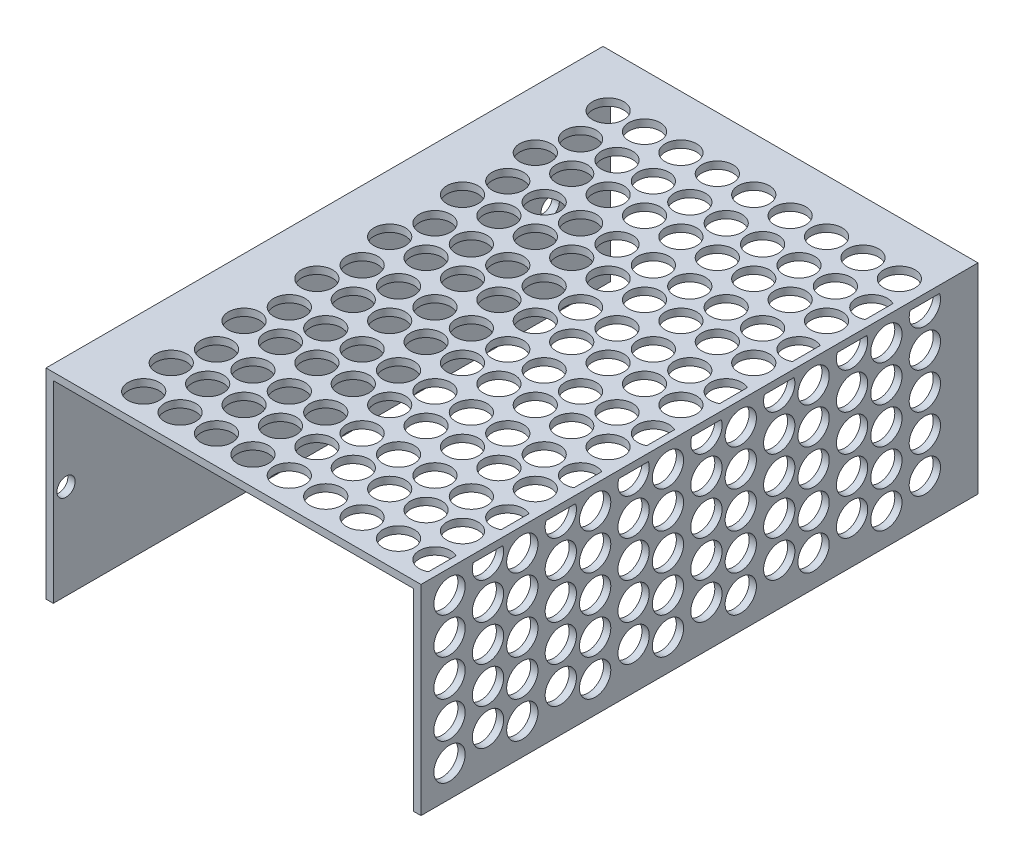
SolidWorks part; units mm, degrees
ref_plane "Спереди" through (0, 0, 0) normal (0, 0, 1) x (1, 0, 0)
ref_plane "Сверху" through (0, 0, 0) normal (0, 1, 0) x (1, 0, 0)
ref_plane "Справа" through (0, 0, 0) normal (1, 0, 0) x (0, 0, -1)
sketch "Эскиз1" plane through (0, 0, 0) normal (0, 0, 1) x (1, 0, 0)
  line L0 (50.5, 0) -> (50.5, 27.5)
  line L1 (50.5, 27.5) -> (1, 27.5)
  line L2 (1, 27.5) -> (1, 0)
  line L3 (0, 0) -> (1, 0)
  line L4 (51.5, 0) -> (51.5, 28.5)
  line L5 (51.5, 28.5) -> (0, 28.5)
  line L6 (0, 28.5) -> (0, 0)
  line L7 (50.5, 0) -> (51.5, 0)
extrude "Бобышка-Вытянуть1" add sketch "Эскиз1" along normal blind 78.5
sketch "Эскиз2" plane through (51.5, 0, 0) normal (1, 0, 0) x (0, 0, -1)
  line L0 (-77.5, 28.5) -> (-77.5, 1)
  line L1 (-78.5, 28.5) -> (0, 28.5) construction
  line L5 (-77.5, 1) -> (-1, 1)
  line L6 (0, 28.5) -> (-1, 28.5)
  line L7 (-1, 28.5) -> (-1, 1)
  line L9 (-77.5, 28.5) -> (-78.5, 28.5)
  line L10 (-78.5, 28.5) -> (-78.5, 0)
  line L12 (-78.5, 0) -> (0, 0)
  line L13 (0, 28.5) -> (0, 0)
extrude "Вырез-Вытянуть1" cut sketch "Эскиз2" against normal through all
sketch "Эскиз3" plane through (0, 28.5, 0) normal (0, 1, 0) x (1, 0, 0)
  line L0 (0, -77.5) -> (0, -1) construction
  line L1 (0, 0) -> (51.5, 0) construction
  line L2 (50.5, -21.6788) -> (50.5, -25.4853)
  line L4 (50.5, -31.6788) -> (50.5, -35.4853)
  line L5 (50.5, -11.6788) -> (50.5, -15.4853)
  line L6 (50.5, -41.6788) -> (50.5, -45.4853)
  line L7 (50.5, -51.6788) -> (50.5, -55.4853)
  line L8 (50.5, -61.6788) -> (50.5, -65.4853)
  line L9 (50.5, -71.6788) -> (50.5, -75.4853)
  circle A0 centre (8, -8.3) radius 2.15
  circle A1 centre (9.5, -13.582) radius 2.15
  circle A2 centre (13, -8.3) radius 2.15
  circle A3 centre (14.5, -13.582) radius 2.15
  circle A4 centre (18, -8.3) radius 2.15
  circle A5 centre (19.5, -13.582) radius 2.15
  circle A6 centre (23, -8.3) radius 2.15
  circle A7 centre (24.5, -13.582) radius 2.15
  circle A8 centre (28, -8.3) radius 2.15
  circle A9 centre (29.5, -13.582) radius 2.15
  circle A10 centre (33, -8.3) radius 2.15
  circle A11 centre (34.5, -13.582) radius 2.15
  circle A12 centre (38, -8.3) radius 2.15
  circle A13 centre (39.5, -13.582) radius 2.15
  circle A14 centre (43, -8.3) radius 2.15
  circle A15 centre (44.5, -13.582) radius 2.15
  circle A16 centre (48, -8.3) radius 2.15
  arc A17 (50.5, -11.6788) -> (50.5, -15.4853) centre (49.5, -13.582) ccw
  circle A18 centre (8, -18.3) radius 2.15
  circle A19 centre (9.5, -23.582) radius 2.15
  circle A20 centre (13, -18.3) radius 2.15
  circle A21 centre (14.5, -23.582) radius 2.15
  circle A22 centre (18, -18.3) radius 2.15
  circle A23 centre (19.5, -23.582) radius 2.15
  circle A24 centre (23, -18.3) radius 2.15
  circle A25 centre (24.5, -23.582) radius 2.15
  circle A26 centre (28, -18.3) radius 2.15
  circle A27 centre (29.5, -23.582) radius 2.15
  circle A28 centre (33, -18.3) radius 2.15
  circle A29 centre (34.5, -23.582) radius 2.15
  circle A30 centre (38, -18.3) radius 2.15
  circle A31 centre (39.5, -23.582) radius 2.15
  circle A32 centre (43, -18.3) radius 2.15
  circle A33 centre (44.5, -23.582) radius 2.15
  circle A34 centre (48, -18.3) radius 2.15
  arc A35 (50.5, -21.6788) -> (50.5, -25.4853) centre (49.5, -23.582) ccw
  circle A36 centre (8, -28.3) radius 2.15
  circle A37 centre (9.5, -33.582) radius 2.15
  circle A38 centre (13, -28.3) radius 2.15
  circle A39 centre (14.5, -33.582) radius 2.15
  circle A40 centre (18, -28.3) radius 2.15
  circle A41 centre (19.5, -33.582) radius 2.15
  circle A42 centre (23, -28.3) radius 2.15
  circle A43 centre (24.5, -33.582) radius 2.15
  circle A44 centre (28, -28.3) radius 2.15
  circle A45 centre (29.5, -33.582) radius 2.15
  circle A46 centre (33, -28.3) radius 2.15
  circle A47 centre (34.5, -33.582) radius 2.15
  circle A48 centre (38, -28.3) radius 2.15
  circle A49 centre (39.5, -33.582) radius 2.15
  circle A50 centre (43, -28.3) radius 2.15
  circle A51 centre (44.5, -33.582) radius 2.15
  circle A52 centre (48, -28.3) radius 2.15
  arc A53 (50.5, -31.6788) -> (50.5, -35.4853) centre (49.5, -33.582) ccw
  circle A54 centre (8, -38.3) radius 2.15
  circle A55 centre (9.5, -43.582) radius 2.15
  circle A56 centre (13, -38.3) radius 2.15
  circle A57 centre (14.5, -43.582) radius 2.15
  circle A58 centre (18, -38.3) radius 2.15
  circle A59 centre (19.5, -43.582) radius 2.15
  circle A60 centre (23, -38.3) radius 2.15
  circle A61 centre (24.5, -43.582) radius 2.15
  circle A62 centre (28, -38.3) radius 2.15
  circle A63 centre (29.5, -43.582) radius 2.15
  circle A64 centre (33, -38.3) radius 2.15
  circle A65 centre (34.5, -43.582) radius 2.15
  circle A66 centre (38, -38.3) radius 2.15
  circle A67 centre (39.5, -43.582) radius 2.15
  circle A68 centre (43, -38.3) radius 2.15
  circle A69 centre (44.5, -43.582) radius 2.15
  circle A70 centre (48, -38.3) radius 2.15
  arc A71 (50.5, -41.6788) -> (50.5, -45.4853) centre (49.5, -43.582) ccw
  circle A72 centre (8, -48.3) radius 2.15
  circle A73 centre (9.5, -53.582) radius 2.15
  circle A74 centre (13, -48.3) radius 2.15
  circle A75 centre (14.5, -53.582) radius 2.15
  circle A76 centre (18, -48.3) radius 2.15
  circle A77 centre (19.5, -53.582) radius 2.15
  circle A78 centre (23, -48.3) radius 2.15
  circle A79 centre (24.5, -53.582) radius 2.15
  circle A80 centre (28, -48.3) radius 2.15
  circle A81 centre (29.5, -53.582) radius 2.15
  circle A82 centre (33, -48.3) radius 2.15
  circle A83 centre (34.5, -53.582) radius 2.15
  circle A84 centre (38, -48.3) radius 2.15
  circle A85 centre (39.5, -53.582) radius 2.15
  circle A86 centre (43, -48.3) radius 2.15
  circle A87 centre (44.5, -53.582) radius 2.15
  circle A88 centre (48, -48.3) radius 2.15
  arc A89 (50.5, -51.6788) -> (50.5, -55.4853) centre (49.5, -53.582) ccw
  circle A90 centre (8, -58.3) radius 2.15
  circle A91 centre (9.5, -63.582) radius 2.15
  circle A92 centre (13, -58.3) radius 2.15
  circle A93 centre (14.5, -63.582) radius 2.15
  circle A94 centre (18, -58.3) radius 2.15
  circle A95 centre (19.5, -63.582) radius 2.15
  circle A96 centre (23, -58.3) radius 2.15
  circle A97 centre (24.5, -63.582) radius 2.15
  circle A98 centre (28, -58.3) radius 2.15
  circle A99 centre (29.5, -63.582) radius 2.15
  circle A100 centre (33, -58.3) radius 2.15
  circle A101 centre (34.5, -63.582) radius 2.15
  circle A102 centre (38, -58.3) radius 2.15
  circle A103 centre (39.5, -63.582) radius 2.15
  circle A104 centre (43, -58.3) radius 2.15
  circle A105 centre (44.5, -63.582) radius 2.15
  circle A106 centre (48, -58.3) radius 2.15
  arc A107 (50.5, -61.6788) -> (50.5, -65.4853) centre (49.5, -63.582) ccw
  circle A108 centre (8, -68.3) radius 2.15
  circle A109 centre (9.5, -73.582) radius 2.15
  circle A110 centre (13, -68.3) radius 2.15
  circle A111 centre (14.5, -73.582) radius 2.15
  circle A112 centre (18, -68.3) radius 2.15
  circle A113 centre (19.5, -73.582) radius 2.15
  circle A114 centre (23, -68.3) radius 2.15
  circle A115 centre (24.5, -73.582) radius 2.15
  circle A116 centre (28, -68.3) radius 2.15
  circle A117 centre (29.5, -73.582) radius 2.15
  circle A118 centre (33, -68.3) radius 2.15
  circle A119 centre (34.5, -73.582) radius 2.15
  circle A120 centre (38, -68.3) radius 2.15
  circle A121 centre (39.5, -73.582) radius 2.15
  circle A122 centre (43, -68.3) radius 2.15
  circle A123 centre (44.5, -73.582) radius 2.15
  circle A124 centre (48, -68.3) radius 2.15
  arc A125 (50.5, -71.6788) -> (50.5, -75.4853) centre (49.5, -73.582) ccw
  dimension "D1" = 4.3
  dimension "D3" = 8.3
  dimension "D4" = 4.3
  dimension "D2" = 8
  dimension "D5" = 1.5
  dimension "D6" = 9
  dimension "D7" = 7
extrude "Вырез-Вытянуть2" cut sketch "Эскиз3" against normal blind 10
hole_wizard "Отверстие обработанное метчиком M31" positions "Эскиз4" profile "Эскиз5" tap size "M3" standard "ISO"
sketch "Эскиз4" plane through (0, 0, 0) normal (-1, 0, 0) x (0, 0, 1)
  line L0 (78.5, 0) -> (78.5, 28.5) construction
  line L1 (0, 0) -> (78.5, 0) construction
  point P0 (75.75, 14)
  point P2 (9.25, 14)
  dimension "D1" = 0
  dimension "D2" = 66.5
  dimension "D3" = 2.75
  dimension "D4" = 14
sketch "Эскиз5" plane through (0, 14, 75.75) normal (0, 1, 0) x (0, 0, 1)
  line L0 (0, 0) -> (0, 9.2511)
  line L1 (0, 9.2511) -> (1.25, 8.5)
  line L2 (1.25, 8.5) -> (1.25, 0)
  line L5 (1.25, 0) -> (0, 0)
  line L10 (0, 9.2511) -> (-1.25, 8.5) construction
  line L11 (0, -6.35) -> (0, 107.95) construction
  dimension "Диаметр сверла" = 2.5
  dimension "Глубина сверла" = 8.5
  dimension "Угол заточки сверла" = 118
cosmetic thread "Отверстие резьбы1" parameters "D1"=1, "D2"=3
cosmetic thread "Отверстие резьбы2" parameters "D1"=1, "D2"=3
sketch "Эскиз6" plane through (51.5, 0, 0) normal (1, 0, 0) x (0, 0, -1)
  line L16 (-60.3212, 27.5) -> (-56.2747, 27.5)
  line L18 (-70.3212, 27.5) -> (-66.2747, 27.5)
  line L19 (-50.3212, 27.5) -> (-46.2747, 27.5)
  line L20 (-40.3212, 27.5) -> (-36.2747, 27.5)
  line L21 (-30.3212, 27.5) -> (-26.2747, 27.5)
  line L22 (-20.3212, 27.5) -> (-16.2747, 27.5)
  line L23 (-10.3212, 27.5) -> (-6.2747, 27.5)
  circle A126 centre (-73.58, 5.2727) radius 2.15
  circle A127 centre (-68.298, 6.7727) radius 2.15
  circle A128 centre (-73.58, 10.2727) radius 2.15
  circle A129 centre (-68.298, 11.7727) radius 2.15
  circle A130 centre (-73.58, 15.2727) radius 2.15
  circle A131 centre (-68.298, 16.7727) radius 2.15
  circle A132 centre (-73.58, 20.2727) radius 2.15
  circle A133 centre (-68.298, 21.7727) radius 2.15
  circle A134 centre (-73.58, 25.2727) radius 2.15
  arc A135 (-70.3212, 27.5) -> (-66.2747, 27.5) centre (-68.298, 26.7727) ccw
  circle A144 centre (-63.58, 5.2727) radius 2.15
  circle A145 centre (-58.298, 6.7727) radius 2.15
  circle A146 centre (-63.58, 10.2727) radius 2.15
  circle A147 centre (-58.298, 11.7727) radius 2.15
  circle A148 centre (-63.58, 15.2727) radius 2.15
  circle A149 centre (-58.298, 16.7727) radius 2.15
  circle A150 centre (-63.58, 20.2727) radius 2.15
  circle A151 centre (-58.298, 21.7727) radius 2.15
  circle A152 centre (-63.58, 25.2727) radius 2.15
  arc A153 (-60.3212, 27.5) -> (-56.2747, 27.5) centre (-58.298, 26.7727) ccw
  circle A162 centre (-53.58, 5.2727) radius 2.15
  circle A163 centre (-48.298, 6.7727) radius 2.15
  circle A164 centre (-53.58, 10.2727) radius 2.15
  circle A165 centre (-48.298, 11.7727) radius 2.15
  circle A166 centre (-53.58, 15.2727) radius 2.15
  circle A167 centre (-48.298, 16.7727) radius 2.15
  circle A168 centre (-53.58, 20.2727) radius 2.15
  circle A169 centre (-48.298, 21.7727) radius 2.15
  circle A170 centre (-53.58, 25.2727) radius 2.15
  arc A171 (-50.3212, 27.5) -> (-46.2747, 27.5) centre (-48.298, 26.7727) ccw
  circle A180 centre (-43.58, 5.2727) radius 2.15
  circle A181 centre (-38.298, 6.7727) radius 2.15
  circle A182 centre (-43.58, 10.2727) radius 2.15
  circle A183 centre (-38.298, 11.7727) radius 2.15
  circle A184 centre (-43.58, 15.2727) radius 2.15
  circle A185 centre (-38.298, 16.7727) radius 2.15
  circle A186 centre (-43.58, 20.2727) radius 2.15
  circle A187 centre (-38.298, 21.7727) radius 2.15
  circle A188 centre (-43.58, 25.2727) radius 2.15
  arc A189 (-40.3212, 27.5) -> (-36.2747, 27.5) centre (-38.298, 26.7727) ccw
  circle A198 centre (-33.58, 5.2727) radius 2.15
  circle A199 centre (-28.298, 6.7727) radius 2.15
  circle A200 centre (-33.58, 10.2727) radius 2.15
  circle A201 centre (-28.298, 11.7727) radius 2.15
  circle A202 centre (-33.58, 15.2727) radius 2.15
  circle A203 centre (-28.298, 16.7727) radius 2.15
  circle A204 centre (-33.58, 20.2727) radius 2.15
  circle A205 centre (-28.298, 21.7727) radius 2.15
  circle A206 centre (-33.58, 25.2727) radius 2.15
  arc A207 (-30.3212, 27.5) -> (-26.2747, 27.5) centre (-28.298, 26.7727) ccw
  circle A216 centre (-23.58, 5.2727) radius 2.15
  circle A217 centre (-18.298, 6.7727) radius 2.15
  circle A218 centre (-23.58, 10.2727) radius 2.15
  circle A219 centre (-18.298, 11.7727) radius 2.15
  circle A220 centre (-23.58, 15.2727) radius 2.15
  circle A221 centre (-18.298, 16.7727) radius 2.15
  circle A222 centre (-23.58, 20.2727) radius 2.15
  circle A223 centre (-18.298, 21.7727) radius 2.15
  circle A224 centre (-23.58, 25.2727) radius 2.15
  arc A225 (-20.3212, 27.5) -> (-16.2747, 27.5) centre (-18.298, 26.7727) ccw
  circle A234 centre (-13.58, 5.2727) radius 2.15
  circle A235 centre (-8.298, 6.7727) radius 2.15
  circle A236 centre (-13.58, 10.2727) radius 2.15
  circle A237 centre (-8.298, 11.7727) radius 2.15
  circle A238 centre (-13.58, 15.2727) radius 2.15
  circle A239 centre (-8.298, 16.7727) radius 2.15
  circle A240 centre (-13.58, 20.2727) radius 2.15
  circle A241 centre (-8.298, 21.7727) radius 2.15
  circle A242 centre (-13.58, 25.2727) radius 2.15
  arc A243 (-10.3212, 27.5) -> (-6.2747, 27.5) centre (-8.298, 26.7727) ccw
extrude "Вырез-Вытянуть3" cut sketch "Эскиз6" against normal blind 24
